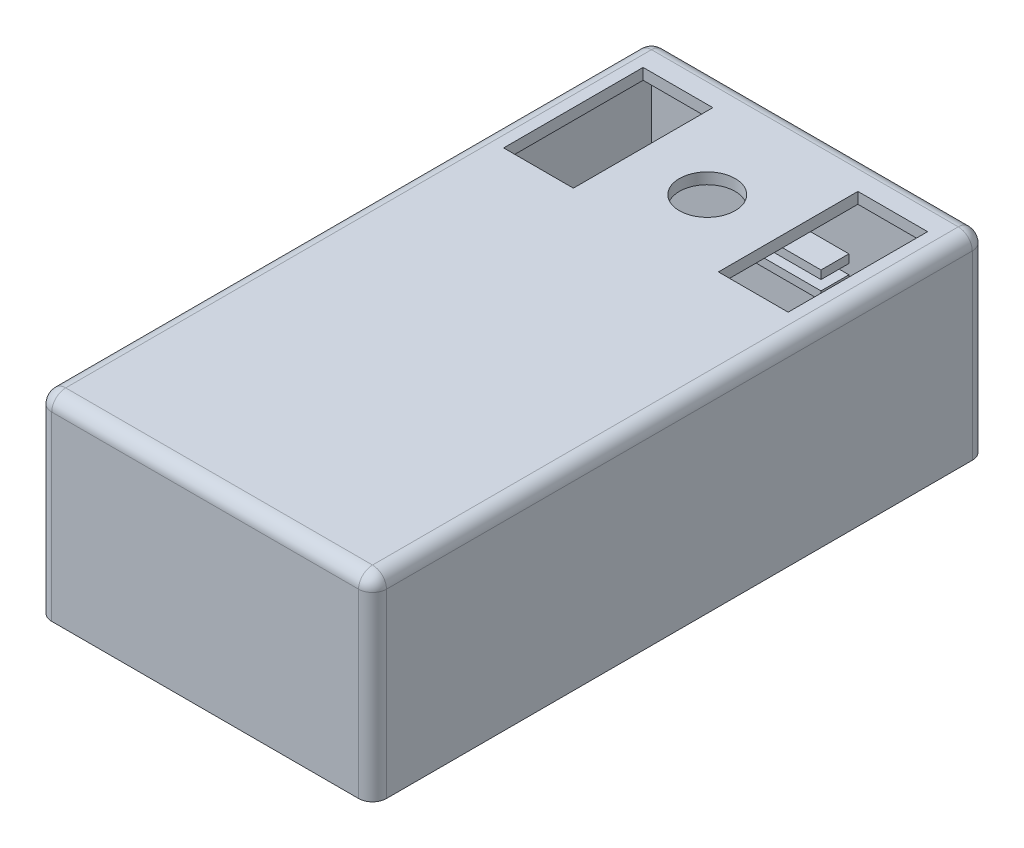
SolidWorks part; units mm, degrees
ref_plane "Front Plane" through (0, 0, 0) normal (0, 0, 1) x (1, 0, 0)
ref_plane "Top Plane" through (0, 0, 0) normal (0, 1, 0) x (1, 0, 0)
ref_plane "Right Plane" through (0, 0, 0) normal (1, 0, 0) x (0, 0, -1)
sketch "Sketch1" plane through (0, 0, 0) normal (0, 1, 0) x (1, 0, 0)
  line L1 (0, 0) -> (60, 0)
  line L2 (0, 0) -> (0, 110)
  line L3 (0, 110) -> (60, 110)
  line L4 (60, 0) -> (60, 110)
  dimension "D1" = 60
  dimension "D2" = 110
extrude "Boss-Extrude1" add sketch "Sketch1" along normal blind 35
sketch "Sketch2" plane through (0, 0, 0) normal (0, -1, 0) x (1, 0, 0)
  line L0 (0, 0) -> (60, 0) construction
  line L1 (2, -2) -> (58, -2)
  line L2 (2, -2) -> (2, -108)
  line L3 (2, -108) -> (58, -108)
  line L4 (58, -2) -> (58, -108)
  line L5 (0, -110) -> (0, 0) construction
  line L6 (60, 0) -> (60, -110) construction
  line L7 (60, -110) -> (0, -110) construction
  dimension "D1" = 2
  dimension "D2" = 2
  dimension "D3" = 2
  dimension "D4" = 2
extrude "Cut-Extrude1" cut sketch "Sketch2" against normal blind 33
sketch "Sketch3" plane through (0, 33, 0) normal (0, -1, 0) x (1, 0, 0)
  line L0 (0, 0) -> (60, 0) construction
  line L1 (0, -110) -> (0, 0) construction
  line L2 (60, 0) -> (60, -110) construction
  line L3 (60, -110) -> (0, -110) construction
  circle A0 centre (7.5, -7.5) radius 1.5
  circle A1 centre (52.5, -7.5) radius 1.5
  circle A2 centre (7.5, -72.5) radius 1.5
  circle A3 centre (52.5, -72.5) radius 1.5
  dimension "D1" = 3
  dimension "D3" = 7.5
  dimension "D4" = 7.5
  dimension "D5" = 7.5
  dimension "D6" = 3
  dimension "D7" = 3
  dimension "D8" = 3
  dimension "D9" = 7.5
  dimension "D10" = 37.5
  dimension "D11" = 7.5
  dimension "D12" = 37.5
  dimension "D2" = 7.5
extrude "Boss-Extrude2" add sketch "Sketch3" along normal blind 36
sketch "Sketch4" plane through (0, 35, 0) normal (0, 1, 0) x (1, 0, 0)
  line L0 (2, 2) -> (2, 108) construction
  line L1 (4.5, 104) -> (17, 104)
  line L2 (4.5, 104) -> (4.5, 79)
  line L3 (4.5, 79) -> (17, 79)
  line L4 (17, 104) -> (17, 85.965)
  line L5 (43, 104) -> (55.5, 104)
  line L6 (43, 104) -> (43, 85.965)
  line L7 (43, 79) -> (55.5, 79)
  line L8 (55.5, 104) -> (55.5, 79)
  line L9 (2, 108) -> (58, 108) construction
  line L10 (58, 108) -> (58, 2) construction
  line L11 (17, 85.965) -> (17, 79)
  line L12 (43, 85.965) -> (43, 79)
  point P14 (37.5, 86.4474)
  point P15 (22.5, 86.6024)
  dimension "D1" = 12.5
  dimension "D2" = 12.5
  dimension "D3" = 25
  dimension "D4" = 25
  dimension "D5" = 2.5
  dimension "D6" = 4
  dimension "D7" = 4
  dimension "D8" = 2.5
extrude "Cut-Extrude2" cut sketch "Sketch4" against normal blind 21
sketch "Sketch6" plane through (0, 35, 0) normal (0, 1, 0) x (1, 0, 0)
  line L0 (17, 79) -> (17, 104) construction
  line L2 (60, 110) -> (0, 110) construction
  circle A0 centre (30, 90) radius 5
  dimension "D1" = 20
  dimension "D2" = 10
  dimension "D3" = 13
extrude "Cut-Extrude3" cut sketch "Sketch6" against normal blind 21
sketch "Sketch7" plane through (0, 0, -110) normal (0, 0, -1) x (-1, 0, 0)
  line L4 (-60, 0) -> (0, 0) construction
  line L5 (-34, 0) -> (-26, 0)
  line L6 (-34, 0) -> (-34, 3.25)
  line L7 (-34, 3.25) -> (-26, 3.25)
  line L8 (-26, 0) -> (-26, 3.25)
  line L9 (-60, 35) -> (-60, 0) construction
  dimension "D1" = 3.25
  dimension "D2" = 8
  dimension "D3" = 26
extrude "Cut-Extrude4" cut sketch "Sketch7" against normal blind 21
sketch "Sketch8" plane through (0, 0, 0) normal (0, -1, 0) x (1, 0, 0)
  line L0 (2, -108) -> (58, -108) construction
  line L1 (23.5, -108) -> (36.5, -108)
  line L2 (23.5, -108) -> (23.5, -109)
  line L3 (23.5, -109) -> (36.5, -109)
  line L4 (36.5, -108) -> (36.5, -109)
  line L5 (26, -108) -> (26, -110) construction
  line L6 (34, -108) -> (34, -110) construction
  dimension "D1" = 1
  dimension "D2" = 2.5
  dimension "D3" = 2.5
extrude "Cut-Extrude5" cut sketch "Sketch8" against normal up to vertex (3.25 mm away)
fillet "Fillet1" radius 2.5 8 edges at (30, 35, -110) (0, 35, -55) (30, 35, 0) (60, 35, -55) (60, 17.5, 0) (0, 17.5, 0) (60, 17.5, -110) (0, 17.5, -110)
sketch "Sketch9" plane through (0, 33, 0) normal (0, -1, 0) x (1, 0, 0)
  line L0 (19.5, -10.1116) -> (19.5, -16.1116)
  line L1 (19.5, -16.1116) -> (24.5, -16.1116)
  line L2 (24.5, -16.1116) -> (24.5, -13.1116)
  line L3 (24.5, -13.1116) -> (34.5, -13.1116)
  line L4 (34.5, -13.1116) -> (34.5, -18.1116)
  line L5 (34.5, -18.1116) -> (40.5, -18.1116)
  line L6 (40.5, -18.1116) -> (40.5, -10.1116)
  line L7 (40.5, -10.1116) -> (19.5, -10.1116)
  line L8 (58, -108) -> (58, -2) construction
  line L11 (34.5, -24.1116) -> (40.5, -24.1116)
  line L12 (34.5, -24.1116) -> (34.5, -32.1116)
  line L13 (34.5, -32.1116) -> (40.5, -32.1116)
  line L14 (40.5, -24.1116) -> (40.5, -32.1116)
  dimension "D1" = 8
  dimension "D2" = 6
  dimension "D3" = 5
  dimension "D4" = 6
  dimension "D5" = 3
  dimension "D6" = 10
  dimension "D7" = 17.5
  dimension "D8" = 6
  dimension "D9" = 8
extrude "Boss-Extrude3" add sketch "Sketch9" along normal blind 5
ref_plane "Plane1" through (0, 29, 0) normal (0, -1, 0) x (-1, 0, 0)
sketch "Sketch10" plane through (0, 29, 0) normal (0, -1, 0) x (-1, 0, 0)
  line L0 (-40.5, 32.1116) -> (-40.5, 24.1116) construction
  line L1 (-38.5, 31.1116) -> (-20.5, 31.1116)
  line L2 (-38.5, 31.1116) -> (-38.5, 11.1116)
  line L3 (-38.5, 11.1116) -> (-20.5, 11.1116)
  line L4 (-20.5, 31.1116) -> (-20.5, 11.1116)
  line L5 (-40.5, 10.1116) -> (-19.5, 10.1116) construction
  line L6 (-19.5, 10.1116) -> (-19.5, 16.1116) construction
  line L7 (-34.5, 32.1116) -> (-40.5, 32.1116) construction
  dimension "D1" = 2
  dimension "D2" = 1
  dimension "D3" = 1
  dimension "D4" = 1
extrude "Cut-Extrude6" cut sketch "Sketch10" against normal blind 1.35
sketch "Sketch11" plane through (0, 30.35, 0) normal (0, -1, 0) x (1, 0, 0)
  line L0 (38.5, -11.1116) -> (20.5, -11.1116) construction
  line L1 (21.7482, -11.1116) -> (17.0458, -11.1116)
  line L2 (21.7482, -11.1116) -> (21.7482, -18.7172)
  line L3 (21.7482, -18.7172) -> (17.0458, -18.7172)
  line L4 (17.0458, -11.1116) -> (17.0458, -18.7172)
  dimension "D1" = 0
extrude "Cut-Extrude7" cut sketch "Sketch11" along normal up to vertex (1.35 mm away)
sketch "Sketch12" plane through (0, 28, 0) normal (0, -1, 0) x (1, 0, 0)
  line L1 (19.5, -10.1116) -> (40.5, -10.1116)
  line L2 (19.5, -10.1116) -> (19.5, -32.1116)
  line L3 (19.5, -32.1116) -> (40.5, -32.1116)
  line L4 (40.5, -10.1116) -> (40.5, -32.1116)
sketch "Sketch13" plane through (0, 0, -108) normal (0, 0, 1) x (1, 0, 0)
  line L0 (2, 0) -> (23.5, 0) construction
  line L1 (22.3889, 20.5) -> (37.3889, 20.5)
  line L2 (22.3889, 20.5) -> (22.3889, 19)
  line L3 (22.3889, 19) -> (37.3889, 19)
  line L4 (37.3889, 20.5) -> (37.3889, 19)
  line L5 (22.3889, 17.25) -> (37.3889, 17.25)
  line L6 (22.3889, 17.25) -> (22.3889, 15.75)
  line L7 (22.3889, 15.75) -> (37.3889, 15.75)
  line L8 (37.3889, 17.25) -> (37.3889, 15.75)
  dimension "D1" = 1.5
  dimension "D2" = 1.5
  dimension "D3" = 0
  dimension "D4" = 0
  dimension "D5" = 15
  dimension "D6" = 15.75
  dimension "D7" = 1.75
extrude "Boss-Extrude4" add sketch "Sketch13" along normal blind 5
chamfer "Chamfer1" distance 2 angle 45 1 edges at (29.8889, 15.75, -108)
sketch "Sketch14" plane through (0, 28, 0) normal (0, -1, 0) x (1, 0, 0)
  line L0 (19.5, -16.1116) -> (24.5, -16.1116) construction
  line L1 (24.5, -13.1116) -> (23.5, -13.1116)
  line L2 (24.5, -13.1116) -> (24.5, -16.1116)
  line L3 (24.5, -16.1116) -> (23.5, -16.1116)
  line L4 (23.5, -13.1116) -> (23.5, -16.1116)
  dimension "D1" = 1
extrude "Cut-Extrude9" cut sketch "Sketch14" against normal up to vertex
